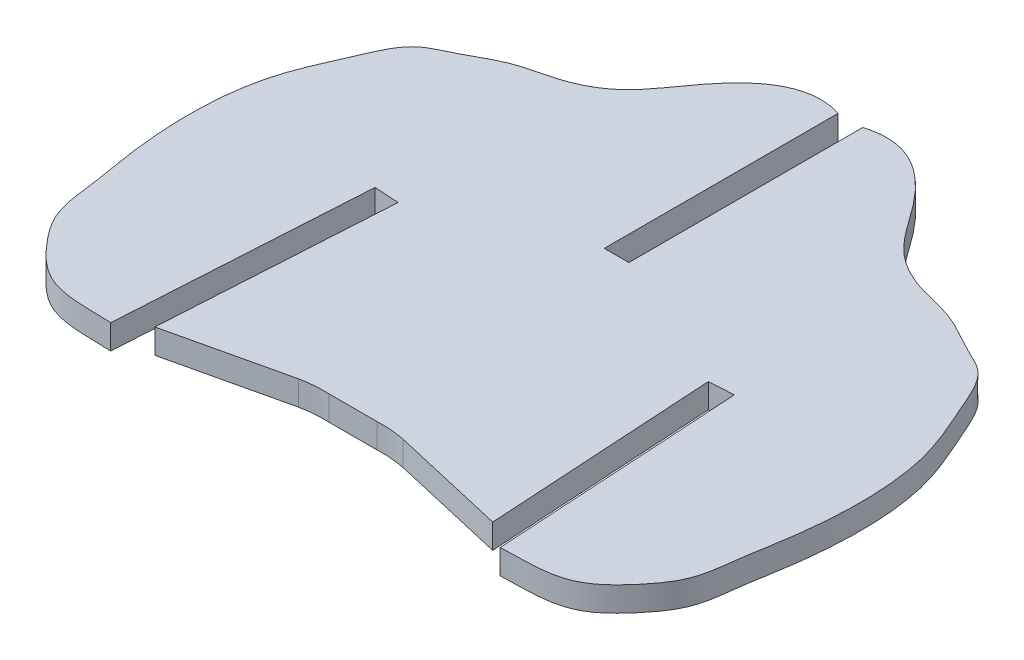
SolidWorks part; units mm, degrees
ref_plane "Спереди" through (0, 0, 0) normal (0, 0, 1) x (1, 0, 0)
ref_plane "Сверху" through (0, 0, 0) normal (0, 1, 0) x (1, 0, 0)
ref_plane "Справа" through (0, 0, 0) normal (1, 0, 0) x (0, 0, -1)
sketch "Эскиз1" plane through (0, 0, 0) normal (0, 1, 0) x (1, 0, 0)
  line L0 (67.558, 140.4457) -> (334.2247, 140.4457) construction
  line L12 (322.5062, 279.217) -> (322.5062, 241.1483)
  line L17 (322.5062, 241.1483) -> (326.5062, 241.1483)
  line L19 (292.816, 190.5037) -> (295.2676, 231.0772)
  line L20 (295.2676, 231.0772) -> (299.2603, 230.836)
  line L21 (299.2603, 230.836) -> (297.0035, 193.4865)
  line L22 (326.5062, 279.217) -> (326.5062, 241.1483)
  line L23 (356.1964, 190.5037) -> (353.7448, 231.0772)
  line L24 (353.7448, 231.0772) -> (349.7521, 230.836)
  line L25 (349.7521, 230.836) -> (352.0089, 193.4865)
  spline S4 degree 3 poles (322.5062, 279.217) (315.784, 281.3118) (308.2297, 274.4994) (302.3272, 264.6164) (295.4056, 261.0755) (288.5722, 259.9982) (283.5976, 256.7127) (277.748, 254.2663) (274.8622, 247.2272) (270.8659, 238.8863) (269.3409, 226.5777) (270.3158, 216.621) (271.9561, 207.8402) (272.3047, 201.865) (276.5096, 196.1278) (281.1409, 191.4728) (287.3938, 190.5102) (291.1472, 190.6045) (292.816, 190.5037) knots 0 0 0 0 0.136915 0.211026 0.260495 0.308388 0.367334 0.395725 0.449167 0.529311 0.610955 0.727156 0.756821 0.816073 0.859026 0.916881 0.959528 1 1 1 1
  spline S5 degree 1 poles (297.0035, 193.4865) (316.0386, 197.8795) knots 0 0 1 1
  spline S12 degree 2 poles (316.0386, 197.8795) (318.2889, 198.329) (320.5717, 198.2351) knots 0 0 0 1 1 1
  spline S13 degree 1 poles (320.5717, 198.2351) (324.5062, 198.2351) knots 0 0 1 1
  spline S14 degree 3 poles (326.5062, 279.217) (333.2283, 281.3118) (340.7827, 274.4994) (346.6851, 264.6164) (353.6068, 261.0755) (360.4402, 259.9982) (365.4148, 256.7127) (371.2643, 254.2663) (374.1502, 247.2272) (378.1465, 238.8863) (379.6714, 226.5777) (378.6966, 216.621) (377.0563, 207.8402) (376.7077, 201.865) (372.5028, 196.1278) (367.8715, 191.4728) (361.6186, 190.5102) (357.8651, 190.6045) (356.1964, 190.5037) knots 0 0 0 0 0.136915 0.211026 0.260495 0.308388 0.367334 0.395725 0.449167 0.529311 0.610955 0.727156 0.756821 0.816073 0.859026 0.916881 0.959528 1 1 1 1
  spline S15 degree 1 poles (328.4407, 198.2351) (324.5062, 198.2351) knots 0 0 1 1
  spline S16 degree 2 poles (332.9738, 197.8795) (330.7235, 198.329) (328.4407, 198.2351) knots 0 0 0 1 1 1
  spline S17 degree 1 poles (352.0089, 193.4865) (332.9738, 197.8795) knots 0 0 1 1
  point P4 (0, 0)
extrude "Бобышка-Вытянуть1" add sketch "Эскиз1" along normal blind 4
